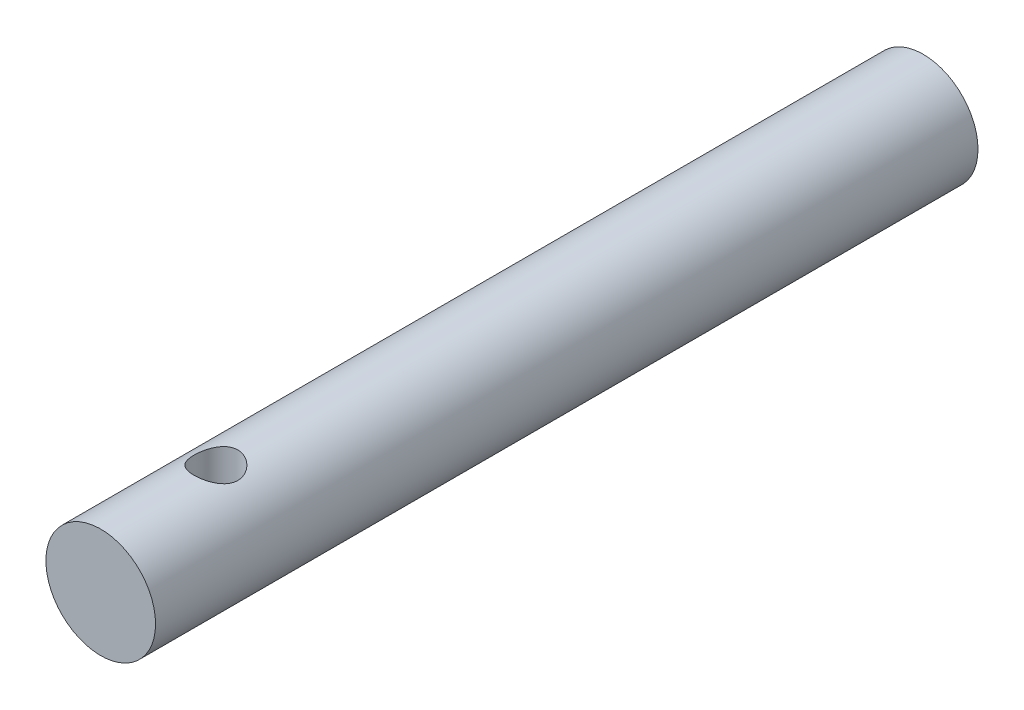
SolidWorks part; units mm, degrees
ref_plane "Спереди" through (0, 0, 0) normal (0, 0, 1) x (1, 0, 0)
ref_plane "Сверху" through (0, 0, 0) normal (0, 1, 0) x (1, 0, 0)
ref_plane "Справа" through (0, 0, 0) normal (1, 0, 0) x (0, 0, -1)
sketch "Эскиз1" plane through (0, 0, 0) normal (0, 0, 1) x (1, 0, 0)
  circle A0 centre (0, 0) radius 10
  dimension "D2" = 20
extrude "Бобышка-Вытянуть1" add sketch "Эскиз1" along normal blind 150
sketch "Эскиз2" plane through (0, 0, 0) normal (0, 1, 0) x (1, 0, 0)
  line L4 (-10, -150) -> (10, -150) construction
  circle A1 centre (0, -129) radius 4
  dimension "D1" = 8
  dimension "D3" = 17
extrude "Вырез-Вытянуть1" cut sketch "Эскиз2" against normal through all both and the other way through all
